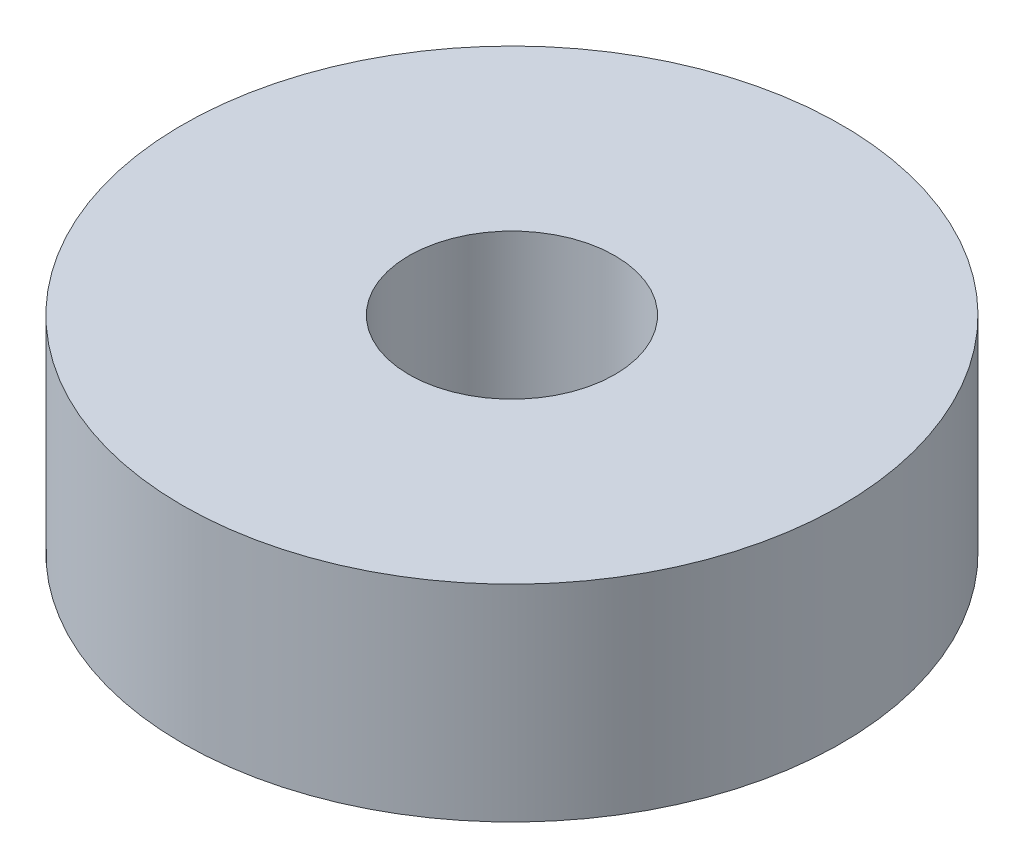
SolidWorks part; units mm, degrees
ref_plane "Front Plane" through (0, 0, 0) normal (0, 0, 1) x (1, 0, 0)
ref_plane "Top Plane" through (0, 0, 0) normal (0, 1, 0) x (1, 0, 0)
ref_plane "Right Plane" through (0, 0, 0) normal (1, 0, 0) x (0, 0, -1)
sketch "Sketch1" plane through (0, 0, 0) normal (0, 1, 0) x (1, 0, 0)
  circle A0 centre (0, 0) radius 2.5
  circle A1 centre (0, 0) radius 8
  dimension "D1" = 5
  dimension "D2" = 16
extrude "Body" add sketch "Sketch1" along normal blind 5
